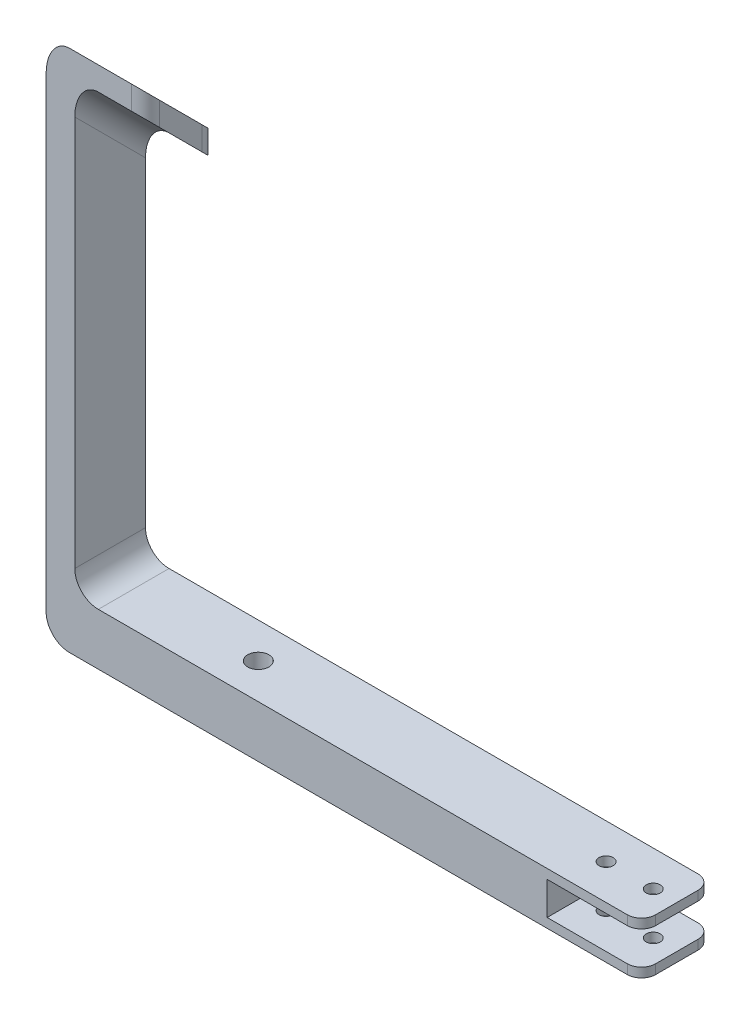
SolidWorks part; units mm, degrees
ref_plane "Alzado" through (0, 0, 0) normal (0, 0, 1) x (1, 0, 0)
ref_plane "Planta" through (0, 0, 0) normal (0, 1, 0) x (1, 0, 0)
ref_plane "Vista lateral" through (0, 0, 0) normal (1, 0, 0) x (0, 0, -1)
sketch "Croquis1" plane through (0, 0, 0) normal (0, 0, 1) x (1, 0, 0)
  line L0 (0, -3.5) -> (0, 3.5)
  line L1 (0, 3.5) -> (20, 3.5)
  line L2 (20, 3.5) -> (20, 5.5)
  line L3 (20, 5.5) -> (-100.18, 5.5)
  line L4 (-100.18, 5.5) -> (-100.18, 85.5)
  line L9 (-100.18, 85.5) -> (-85.18, 85.5)
  line L10 (-85.18, 85.5) -> (-85.18, 105.5)
  line L11 (-85.18, 105.5) -> (-106.25, 105.5)
  line L12 (-106.25, 105.5) -> (-106.25, -5.5)
  line L13 (-106.25, -5.5) -> (20, -5.5)
  line L14 (20, -5.5) -> (20, -3.5)
  line L15 (20, -3.5) -> (0, -3.5)
  dimension "D1" = 3.5
  dimension "D2" = 7
  dimension "D3" = 2
  dimension "D4" = 2
  dimension "D5" = 20
  dimension "D6" = 126.25
  dimension "D7" = 100.18
  dimension "D8" = 15
  dimension "D9" = 20
  dimension "D10" = 80
extrude "Saliente-Extruir1" add sketch "Croquis1" along normal mid plane 15
sketch "Croquis2" plane through (0, 5.5, 0) normal (0, 1, 0) x (1, 0, 0)
  circle A0 centre (15, 0) radius 1.5
  circle A1 centre (5, 0) radius 1.5
  dimension "D2" = 3
  dimension "D3" = 3
  dimension "D1" = 5
  dimension "D4" = 10
extrude "Cortar-Extruir1" cut sketch "Croquis2" against normal through all
fillet "Redondeo1" radius 3 4 edges at (20, -4.5, 7.5) (20, -4.5, -7.5) (20, 4.5, 7.5) (20, 4.5, -7.5)
fillet "Redondeo2" radius 3 2 edges at (-85.18, 95.5, -7.5) (-85.18, 95.5, 7.5)
sketch "Croquis4" plane through (-100.18, 0, 0) normal (1, 0, 0) x (0, 0, -1)
  line L0 (-7.5, 105.5) -> (7.5, 90.5)
  line L1 (-7.5, 85.5) -> (-7.5, 105.5) construction
  line L2 (7.5, 105.5) -> (7.5, 85.5) construction
  line L3 (7.5, 90.5) -> (7.5, 105.5)
  line L4 (7.5, 105.5) -> (-7.5, 105.5)
  line L7 (-7.5, 100.5) -> (7.5, 85.5)
  line L9 (-7.5, 85.5) -> (-7.5, 100.5)
  line L11 (7.5, 85.5) -> (-7.5, 85.5)
  dimension "D1" = 45
  dimension "D2" = 5
extrude "Cortar-Extruir3" cut sketch "Croquis4" along normal through all
sketch "Croquis5" plane through (0, 49, -49) normal (0, 0.7071, -0.7071) x (1, 0, 0)
  line L0 (-106.25, -79.9031) -> (-106.25, -58.6899) construction
  circle A0 centre (-89.98, -69.2965) radius 2.25
  point P6 (-106.25, -69.2965)
  dimension "D1" = 4.5
  dimension "D2" = 10.2
extrude "Cortar-Extruir4" cut sketch "Croquis5" against normal through all
sketch "Croquis6" plane through (-100.18, 0, 0) normal (1, 0, 0) x (0, 0, -1)
  line L3 (7.5, 90.5) -> (7.5, 105.5)
  line L4 (7.5, 90.5) -> (7.5, 105.5)
  line L9 (-7.5, 105.5) -> (7.5, 90.5)
  line L11 (7.5, 105.5) -> (-7.5, 105.5)
  line L13 (-7.5, 105.5) -> (7.5, 90.5)
  line L15 (7.5, 105.5) -> (-7.5, 105.5)
  dimension "D1" = 0
extrude "Cortar-Extruir5" cut sketch "Croquis6" against normal through all
fillet "Redondeo3" radius 5 4 edges at (-106.25, -5.5, 0) (-100.18, 5.5, 0) (-106.25, 98, 0) (-100.18, 93, 0)
sketch "Croquis7" plane through (0, 5.5, 0) normal (0, 1, 0) x (1, 0, 0)
  line L0 (-106.25, 7.5) -> (-106.25, -7.5) construction
  circle A0 centre (-68.75, 0) radius 2.25
  dimension "D1" = 4.5
  dimension "D2" = 37.5
extrude "Cortar-Extruir6" cut sketch "Croquis7" against normal blind 7
